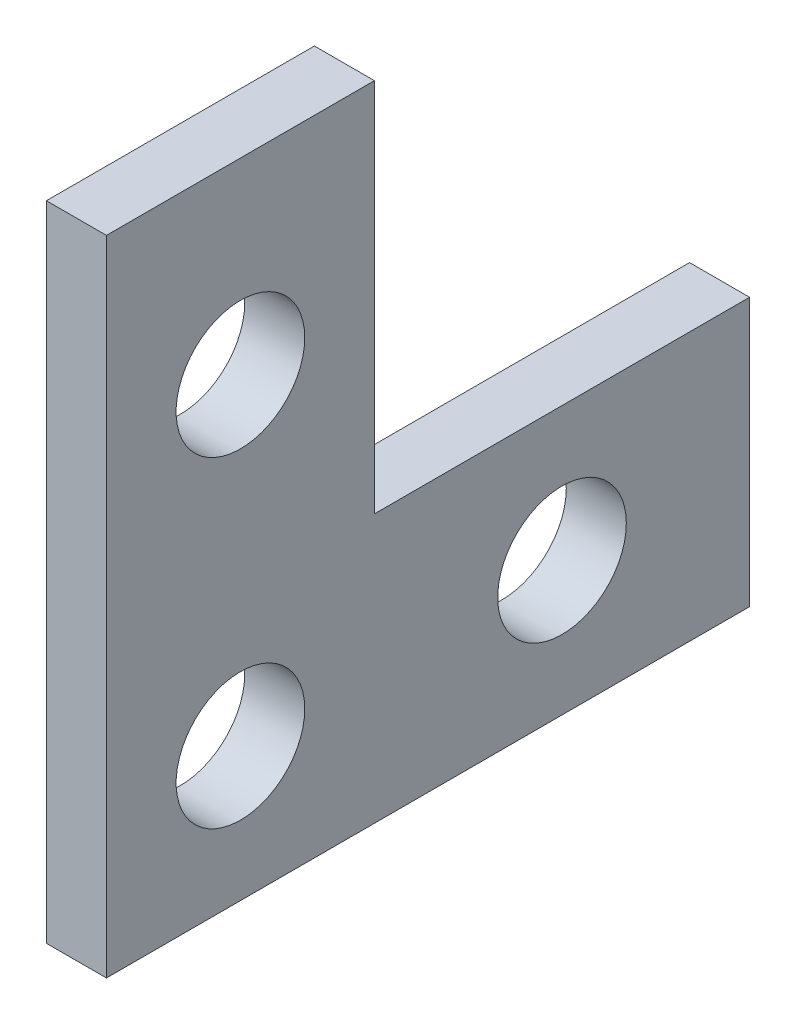
SolidWorks part; units mm, degrees
ref_plane "Alzado" through (0, 0, 0) normal (0, 0, 1) x (1, 0, 0)
ref_plane "Planta" through (0, 0, 0) normal (0, 1, 0) x (1, 0, 0)
ref_plane "Vista lateral" through (0, 0, 0) normal (1, 0, 0) x (0, 0, -1)
sketch "Croquis1" plane through (0, 0, 0) normal (1, 0, 0) x (0, 0, -1)
  line L0 (-7.5, 7.5) -> (-7.5, -7.5)
  line L1 (55, 0) -> (-55, 0) construction
  line L2 (7.5, -7.5) -> (-7.5, -7.5)
  line L3 (7.5, -7.5) -> (7.5, -1.25)
  line L4 (7.5, -1.25) -> (-1.25, -1.25)
  line L5 (0, 55) -> (0, -55) construction
  line L7 (-7.5, 7.5) -> (-1.25, 7.5)
  line L8 (-1.25, 7.5) -> (-1.25, -1.25)
  point P0 (0, -7.5)
  point P2 (-7.5, 0)
  dimension "D1" = 6.25
  dimension "D2" = 6.25
  dimension "D3" = 15
  dimension "D4" = 15
extrude "Saliente-Extruir1" add sketch "Croquis1" along normal mid plane 1.4
sketch "Croquis2" plane through (0.7, 0, 0) normal (1, 0, 0) x (0, 0, -1)
  line L0 (-4.375, 7.5) -> (-4.375, -7.5) construction
  line L1 (-1.25, 7.5) -> (-7.5, 7.5) construction
  line L2 (-7.5, -7.5) -> (7.5, -7.5) construction
  line L3 (7.5, -4.375) -> (-7.5, -4.375) construction
  line L4 (7.5, -7.5) -> (7.5, -1.25) construction
  line L5 (-7.5, 7.5) -> (-7.5, -7.5) construction
  line L6 (3.125, -1.25) -> (3.125, -7.5) construction
  line L7 (7.5, -1.25) -> (-1.25, -1.25) construction
  line L8 (-1.25, 3.125) -> (-7.5, 3.125) construction
  line L9 (-1.25, -1.25) -> (-1.25, 7.5) construction
  line L10 (-1.25, -1.25) -> (-1.25, -7.5) construction
  circle A0 centre (-4.375, -4.375) radius 1.5
  circle A1 centre (-4.375, 3.125) radius 1.5
  circle A2 centre (3.125, -4.375) radius 1.5
  point P12 (-4.375, -4.375)
  point P23 (-4.375, 3.125)
  point P24 (3.125, -4.375)
  point P32 (-1.25, -4.375)
  dimension "D1" = 3
  dimension "D2" = 3
  dimension "D3" = 3
  dimension "D4" = 4.375
  dimension "D5" = 3.125
  dimension "D6" = 7.5
extrude "Cortar-Extruir1" cut sketch "Croquis2" against normal mid plane 20
